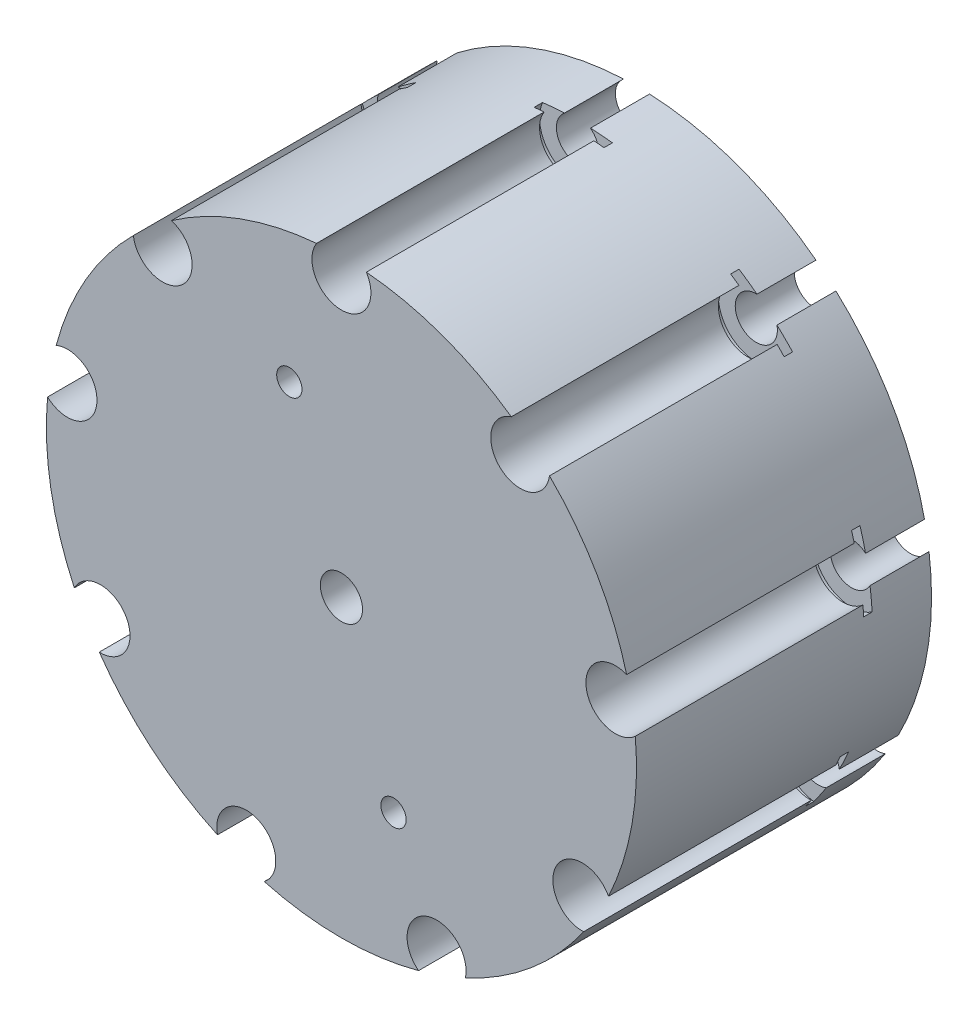
SolidWorks part; units mm, degrees
ref_plane "前视基准面" through (0, 0, 0) normal (0, 0, 1) x (1, 0, 0)
ref_plane "上视基准面" through (0, 0, 0) normal (0, 1, 0) x (1, 0, 0)
ref_plane "右视基准面" through (0, 0, 0) normal (1, 0, 0) x (0, 0, -1)
sketch "草图1" plane through (0, 0, 0) normal (0, 0, 1) x (1, 0, 0)
  circle A0 centre (0, 0) radius 35
  circle A1 centre (0, 0) radius 2.5
  dimension "D1" = 70
  dimension "D2" = 5
extrude "凸台-拉伸1" add sketch "草图1" along normal blind 35
sketch "草图2" plane through (0, 0, 35) normal (0, 0, 1) x (1, 0, 0)
  circle A0 centre (0, 33) radius 3.5
  circle A1 centre (0, 0) radius 35 construction
  dimension "D1" = 7
  dimension "D2" = 33
  dimension "D3" = 33
extrude "切除-拉伸1" cut sketch "草图2" against normal blind 27
sketch "草图3" plane through (0, 0, 8) normal (0, 0, 1) x (1, 0, 0)
  circle A0 centre (0, 33) radius 2.5
  dimension "D1" = 5
extrude "切除-拉伸2" cut sketch "草图3" against normal up to surface (8 mm away) up to face at (35, 0, 0)
sketch "草图5" plane through (0, 0, 8) normal (0, 0, 1) x (1, 0, 0)
  circle A0 centre (0, 33) radius 4.5
  dimension "D1" = 9
extrude "切除-拉伸3" cut sketch "草图5" against normal blind 1
pattern_circular "阵列(圆周)1" count 9 over 360 about axis through (0, 0, 0) along (0, 0, 1) of "切除-拉伸1", "切除-拉伸2", "切除-拉伸3"
sketch "草图6" plane through (0, 0, 0) normal (0, 0, -1) x (-1, 0, 0)
  line L0 (0, 0) -> (6.1803, 19.0211) construction
  line L1 (0, 30.5) -> (0, 0) construction
  line L2 (0, 0) -> (-6.1803, -19.0211) construction
  circle A0 centre (6.1803, 19.0211) radius 1.5
  arc A1 (-1.5444, 34.9659) -> (1.5444, 34.9659) centre (0, 33) ccw construction
  circle A2 centre (-6.1803, -19.0211) radius 1.5
  dimension "D1" = 3
  dimension "D5" = 3
  dimension "D2" = 20
  dimension "D3" = 18
  dimension "D4" = 20
extrude "切除-拉伸4" cut sketch "草图6" against normal up to surface (35 mm away) up to face at (0, 0, 35)
